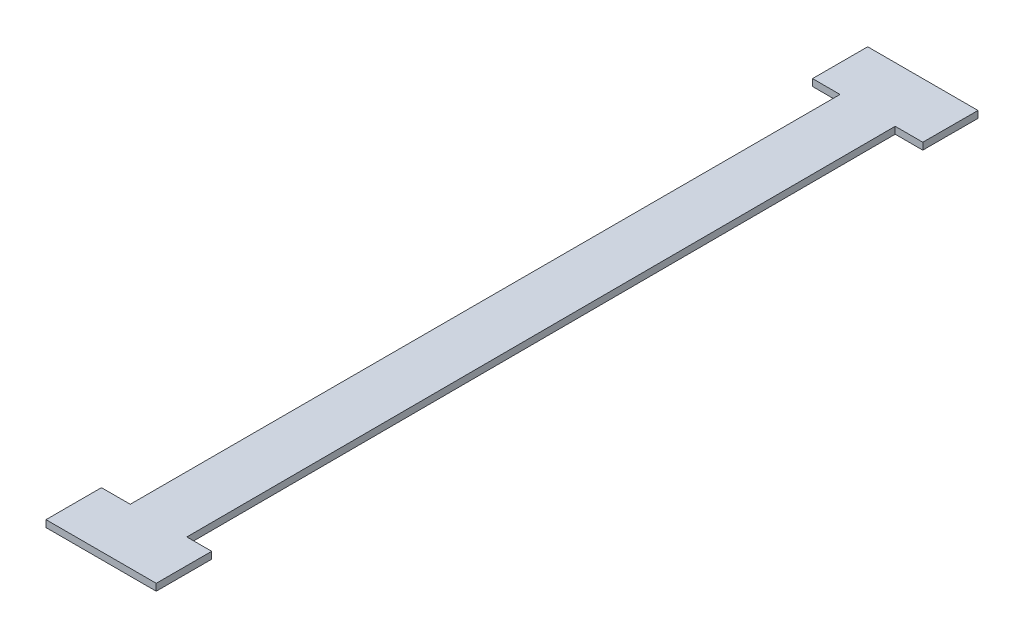
SolidWorks part; units mm, degrees
ref_plane "Front Plane" through (0, 0, 0) normal (0, 0, 1) x (1, 0, 0)
ref_plane "Top Plane" through (0, 0, 0) normal (0, 1, 0) x (1, 0, 0)
ref_plane "Right Plane" through (0, 0, 0) normal (1, 0, 0) x (0, 0, -1)
sketch "Sketch1" plane through (0, 0, 0) normal (0, 1, 0) x (1, 0, 0)
  line L0 (-0.0575, 357.2864) -> (-12.7222, 357.2864)
  line L2 (-0.0575, 357.2864) -> (-0.0575, 30.3973)
  line L3 (-0.0575, 30.3973) -> (-13.3194, 30.3973)
  line L4 (-13.3194, 30.3973) -> (-13.3194, 4.8628)
  line L5 (-12.7222, 357.2864) -> (-12.7222, 382.6725)
  line L6 (-12.7222, 382.6725) -> (38.0842, 382.6725)
  line L7 (38.0842, 382.6725) -> (38.0411, 357.2864)
  line L8 (38.0411, 357.2864) -> (25.3276, 357.2864)
  line L9 (-13.3194, 4.8628) -> (37.4431, 4.8628)
  line L10 (37.4431, 4.8628) -> (37.4431, 30.3973)
  line L11 (37.4431, 30.3973) -> (26.0114, 30.3973)
  line L12 (26.0114, 30.3973) -> (25.3276, 357.2864)
extrude "Boss-Extrude1" add sketch "Sketch1" along normal blind 3.175
